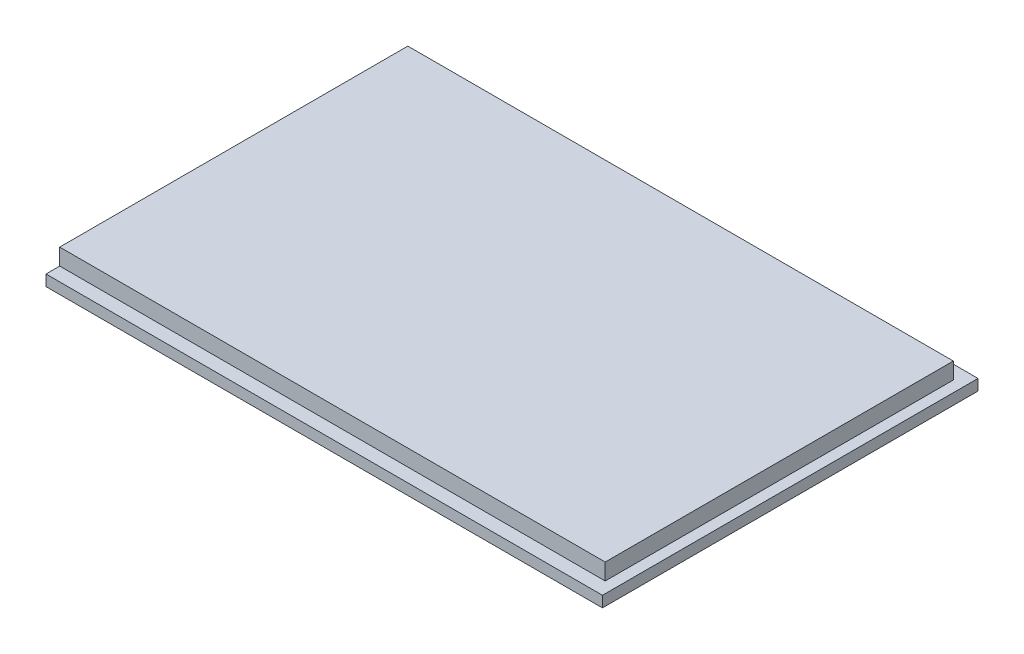
SolidWorks part; units mm, degrees
ref_plane "前视基准面" through (0, 0, 0) normal (0, 0, 1) x (1, 0, 0)
ref_plane "上视基准面" through (0, 0, 0) normal (0, 1, 0) x (1, 0, 0)
ref_plane "右视基准面" through (0, 0, 0) normal (1, 0, 0) x (0, 0, -1)
sketch "草图2" plane through (0, 0, 0) normal (0, 1, 0) x (1, 0, 0)
  line L1 (-20.3, 13.7) -> (20.3, 13.7)
  line L2 (-20.3, 13.7) -> (-20.3, -13.7)
  line L3 (-20.3, -13.7) -> (20.3, -13.7)
  line L4 (20.3, 13.7) -> (20.3, -13.7)
  line L5 (-20.3, 13.7) -> (20.3, -13.7) construction
  line L6 (-20.3, -13.7) -> (20.3, 13.7) construction
  point P0 (0, 0)
  dimension "D1" = 40.6
  dimension "D2" = 27.4
extrude "凸台-拉伸1" add sketch "草图2" along normal blind 0.8
sketch "草图3" plane through (0, 0.8, 0) normal (0, 1, 0) x (1, 0, 0)
  line L0 (-20.3, 13.7) -> (-20.3, -13.7) construction
  line L1 (-20.3, 12.7) -> (19.5, 12.7)
  line L2 (-20.3, 12.7) -> (-20.3, -12.7)
  line L3 (-20.3, -12.7) -> (19.5, -12.7)
  line L4 (19.5, 12.7) -> (19.5, -12.7)
  line L5 (20.3, 13.7) -> (-20.3, 13.7) construction
  line L6 (-20.3, -13.7) -> (20.3, -13.7) construction
  line L7 (20.3, -13.7) -> (20.3, 13.7) construction
  dimension "D1" = 1
  dimension "D2" = 1
  dimension "D3" = 0.8
extrude "凸台-拉伸2" add sketch "草图3" along normal blind 1.2
